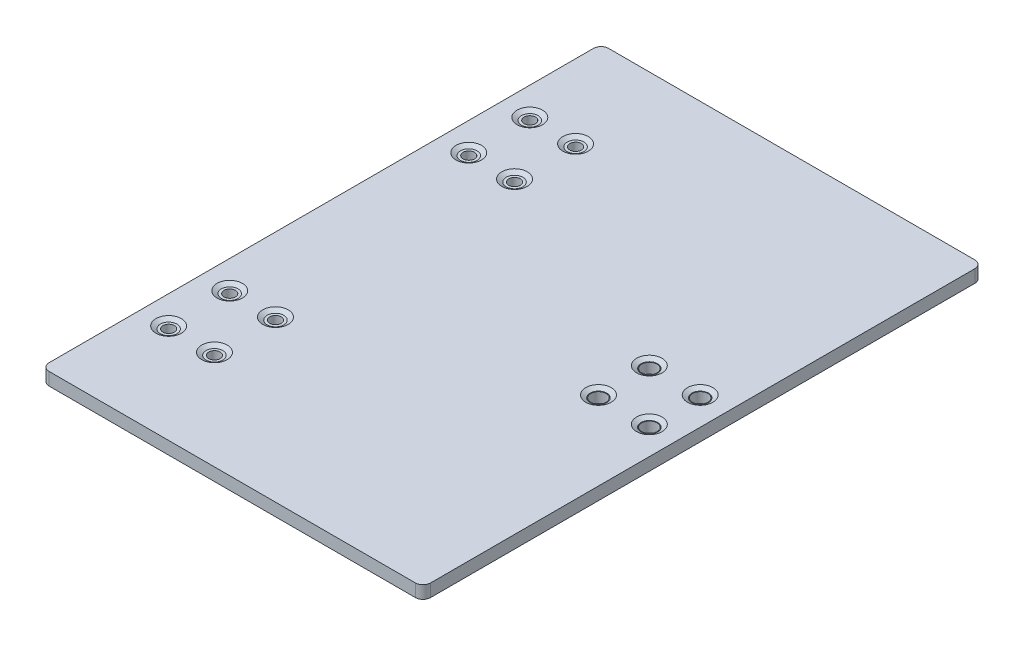
SolidWorks part; units mm, degrees
material "PLA"
ref_plane "Front Plane" through (0, 0, 0) normal (0, 0, 1) x (1, 0, 0)
ref_plane "Top Plane" through (0, 0, 0) normal (0, 1, 0) x (1, 0, 0)
ref_plane "Right Plane" through (0, 0, 0) normal (1, 0, 0) x (0, 0, -1)
sketch "Sketch1" plane through (0, 0, 0) normal (0, 1, 0) x (1, 0, 0)
  line L0 (0, 220) -> (0, 0)
  line L1 (0, 0) -> (150, 0)
  line L2 (150, 0) -> (150, 220)
  line L3 (150, 220) -> (0, 220)
  dimension "D1" = 220
  dimension "D2" = 150
  dimension "D3" = 0
extrude "Boss-Extrude1" add sketch "Sketch1" against normal blind 5
sketch "Sketch2" plane through (0, 0, 0) normal (0, 1, 0) x (1, 0, 0)
  line L1 (0, 220) -> (0, 0) construction
  line L2 (0, 0) -> (150, 0) construction
  line L4 (150, 0) -> (150, 220) construction
  circle A0 centre (11, 181) radius 2.25
  circle A1 centre (11, 157) radius 2.25
  circle A2 centre (29, 157) radius 2.25
  circle A3 centre (29, 181) radius 2.25
  circle A4 centre (11, 63) radius 2.25
  circle A5 centre (29, 63) radius 2.25
  circle A6 centre (11, 39) radius 2.25
  circle A7 centre (29, 39) radius 2.25
  circle A8 centre (119, 120) radius 3
  circle A9 centre (139, 120) radius 3
  circle A10 centre (119, 100) radius 3
  circle A11 centre (139, 100) radius 3
  point P0 (11, 181)
  point P1 (29, 181)
  point P2 (29, 157)
  point P3 (11, 157)
  point P4 (11, 63)
  point P5 (11, 39)
  point P6 (29, 39)
  point P7 (29, 63)
  point P8 (119, 120)
  point P9 (139, 120)
  point P10 (139, 100)
  point P11 (119, 100)
  point P12 (20, 169)
  point P27 (20, 51)
  point P38 (80, 110)
  dimension "D11" = 4.5
  dimension "D12" = 4.5
  dimension "D13" = 4.5
  dimension "D14" = 4.5
  dimension "D26" = 4.5
  dimension "D27" = 4.5
  dimension "D28" = 4.5
  dimension "D29" = 4.5
  dimension "D40" = 6
  dimension "D41" = 6
  dimension "D42" = 6
  dimension "D43" = 6
  dimension "D34" = 10
  dimension "D35" = 10
  dimension "D10" = 142
  dimension "D16" = 39
  dimension "D2" = 9
  dimension "D3" = 9
  dimension "D4" = 18
  dimension "D5" = 18
  dimension "D6" = 24
  dimension "D7" = 24
  dimension "D8" = 12
  dimension "D9" = 12
  dimension "D15" = 11
  dimension "D17" = 12
  dimension "D18" = 12
  dimension "D19" = 11
  dimension "D20" = 9
  dimension "D21" = 9
  dimension "D22" = 9
  dimension "D23" = 9
  dimension "D24" = 12
  dimension "D25" = 12
  dimension "D30" = 20
  dimension "D31" = 20
  dimension "D32" = 11
  dimension "D33" = 11
  dimension "D36" = 10
  dimension "D37" = 10
  dimension "D39" = 110
extrude "Cut-Extrude2" cut sketch "Sketch2" against normal blind 10
sketch "Sketch3" plane through (0, 0, 0) normal (0, 1, 0) x (1, 0, 0)
  circle A0 centre (11, 181) radius 5
  circle A1 centre (29, 181) radius 5
  circle A2 centre (11, 157) radius 5
  circle A3 centre (29, 157) radius 5
  circle A4 centre (119, 120) radius 5
  circle A5 centre (139, 120) radius 5
  circle A6 centre (119, 100) radius 5
  circle A7 centre (139, 100) radius 5
  circle A8 centre (29, 63) radius 5
  circle A9 centre (11, 63) radius 5
  circle A10 centre (11, 39) radius 5
  circle A11 centre (29, 39) radius 5
  dimension "D1" = 10
  dimension "D2" = 10
  dimension "D3" = 10
  dimension "D4" = 10
  dimension "D5" = 10
  dimension "D6" = 10
  dimension "D7" = 10
  dimension "D8" = 10
  dimension "D9" = 10
  dimension "D10" = 10
  dimension "D11" = 10
  dimension "D12" = 10
extrude "Cut-Extrude3" cut sketch "Sketch3" against normal blind 1 draft 60
fillet "Fillet1" radius 3 4 edges at (0, -2.5, -220) (150, -2.5, -220) (150, -2.5, 0) (0, -2.5, 0)
